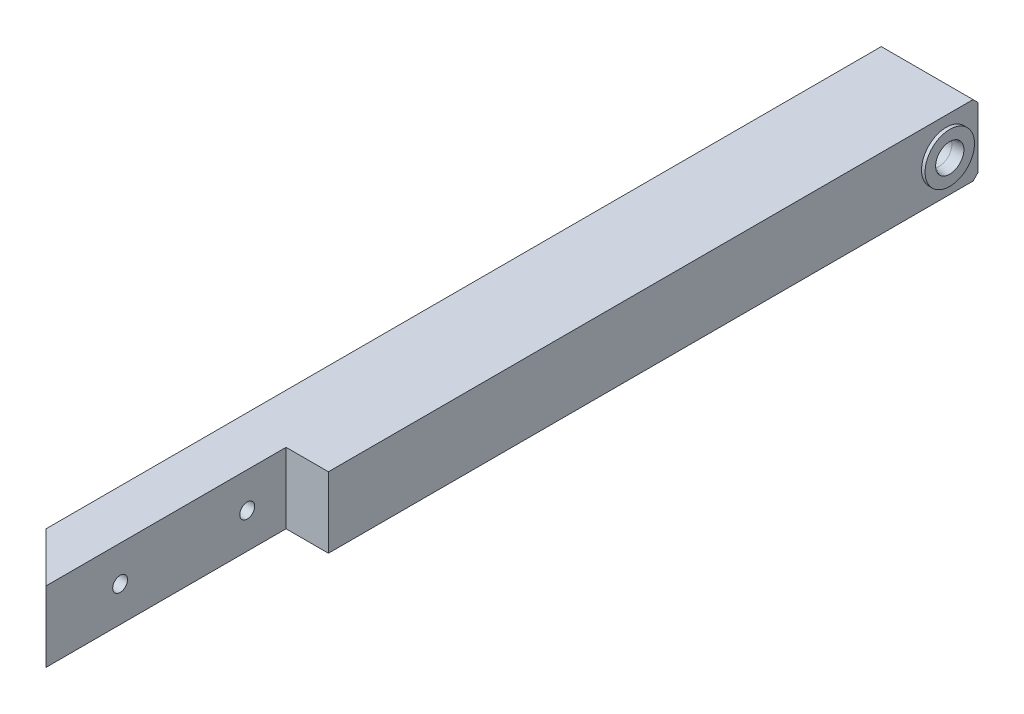
SolidWorks part; units mm, degrees
ref_plane "Front Plane" through (0, 0, 0) normal (0, 0, 1) x (1, 0, 0)
ref_plane "Top Plane" through (0, 0, 0) normal (0, 1, 0) x (1, 0, 0)
ref_plane "Right Plane" through (0, 0, 0) normal (1, 0, 0) x (0, 0, -1)
ref_plane "Plan1" through (0, 10, 0) normal (0, -1, 0) x (1, 0, 0)
sketch "Esquisse1" plane through (0, 10, 0) normal (0, -1, 0) x (1, 0, 0)
  line L0 (28, 25.5) -> (28, 151.5)
  line L1 (28, 151.5) -> (15, 151.5)
  line L2 (15, 151.5) -> (15, 25.5)
  line L3 (15, 25.5) -> (28, 25.5)
extrude "Boss.-Extru.1" add sketch "Esquisse1" against normal blind 10
sketch "Esquisse2" plane through (0, 20, 0) normal (0, 1, 0) x (-1, 0, 0)
  line L0 (-28, 117.5) -> (-22, 117.5)
  line L1 (-22, 117.5) -> (-22, 151.5)
  line L2 (-22, 151.5) -> (-28, 151.5)
  line L3 (-28, 151.5) -> (-28, 117.5)
extrude "Enlèv. mat.-Extru.1" cut sketch "Esquisse2" against normal through all
ref_plane "Plan2" through (0, 11.2, 0) normal (0, -1, 0) x (1, 0, 0)
sketch "Esquisse3" plane through (0, 11.2, 0) normal (0, -1, 0) x (1, 0, 0)
  line L0 (20.8533, 76.2777) -> (21.5573, 76.2788)
  line L1 (21.5573, 76.2788) -> (21.5614, 73.7372)
  line L2 (21.5614, 73.7372) -> (19.3376, 73.7336)
  line L3 (22.822, 73.8272) -> (22.6255, 74.5435)
  line L4 (19.736, 74.5148) -> (20.8533, 74.5148)
  line L5 (20.8533, 74.5148) -> (20.8533, 76.2777)
  arc A0 (19.3376, 73.7336) -> (18.633, 74.9446) centre (22.8239, 76.5726) cw
  spline S0 degree 3 poles (18.633, 74.9446) (18.5989, 75.0481) (18.5308, 75.2546) (18.4496, 75.5709) (18.4126, 75.8954) (18.4027, 76.1126) (18.3977, 76.2215) knots 0 0 0 0 0.250783 0.500014 0.749231 1 1 1 1
  spline S1 degree 3 poles (18.3977, 76.2215) (18.4047, 76.3608) (18.4187, 76.6379) (18.4758, 77.0511) (18.608, 77.4466) (18.72, 77.7004) (18.7763, 77.8279) knots 0 0 0 0 0.251459 0.500134 0.748674 1 1 1 1
  spline S2 degree 3 poles (18.7763, 77.8279) (18.8456, 77.94) (18.983, 78.1621) (19.2264, 78.4709) (19.5361, 78.7134) (19.7587, 78.8498) (19.8711, 78.9186) knots 0 0 0 0 0.2523 0.500035 0.747735 1 1 1 1
  spline S3 degree 3 poles (19.8711, 78.9186) (19.9984, 78.9736) (20.2516, 79.0829) (20.646, 79.2116) (21.0571, 79.2669) (21.3328, 79.2803) (21.4714, 79.287) knots 0 0 0 0 0.251271 0.49985 0.74858 1 1 1 1
  spline S4 degree 3 poles (21.4714, 79.287) (21.6125, 79.2798) (21.8935, 79.2654) (22.3125, 79.209) (22.7157, 79.0817) (22.9758, 78.9745) (23.1064, 78.9207) knots 0 0 0 0 0.251234 0.500055 0.748821 1 1 1 1
  spline S5 degree 3 poles (23.1064, 78.9207) (23.2212, 78.8559) (23.4486, 78.7275) (23.7669, 78.4969) (24.0197, 78.1957) (24.1621, 77.9771) (24.234, 77.8668) knots 0 0 0 0 0.252519 0.50023 0.747709 1 1 1 1
  spline S6 degree 3 poles (24.234, 77.8668) (24.2896, 77.7411) (24.4002, 77.4913) (24.5295, 77.101) (24.5836, 76.6935) (24.5961, 76.4203) (24.6023, 76.2829) knots 0 0 0 0 0.25132 0.499761 0.748442 1 1 1 1
  spline S7 degree 3 poles (24.6023, 76.2829) (24.5987, 76.1825) (24.5915, 75.9823) (24.5605, 75.6831) (24.4868, 75.3914) (24.4234, 75.2015) (24.3915, 75.1062) knots 0 0 0 0 0.250926 0.500139 0.749213 1 1 1 1
  spline S8 degree 3 poles (24.3915, 75.1062) (24.3561, 75.0281) (24.2856, 74.8729) (24.159, 74.6501) (23.991, 74.4565) (23.8668, 74.3401) (23.8042, 74.2815) knots 0 0 0 0 0.251757 0.500316 0.748557 1 1 1 1
  spline S9 degree 3 poles (23.8042, 74.2815) (23.7288, 74.2306) (23.5784, 74.1291) (23.3401, 73.9966) (23.084, 73.9028) (22.9096, 73.8525) (22.822, 73.8272) knots 0 0 0 0 0.250861 0.499685 0.748824 1 1 1 1
  spline S10 degree 3 poles (22.6255, 74.5435) (22.6892, 74.5636) (22.8161, 74.6037) (23.0028, 74.6749) (23.1784, 74.7704) (23.2899, 74.8428) (23.3458, 74.8791) knots 0 0 0 0 0.250917 0.500324 0.749408 1 1 1 1
  spline S11 degree 3 poles (23.3458, 74.8791) (23.3902, 74.9196) (23.4784, 75.0001) (23.5977, 75.1345) (23.6885, 75.2896) (23.7396, 75.3977) (23.7653, 75.4521) knots 0 0 0 0 0.251387 0.499614 0.748228 1 1 1 1
  spline S12 degree 3 poles (23.7653, 75.4521) (23.789, 75.5188) (23.8362, 75.6517) (23.8912, 75.8564) (23.9146, 76.067) (23.9201, 76.208) (23.9229, 76.2788) knots 0 0 0 0 0.250883 0.49987 0.748987 1 1 1 1
  spline S13 degree 3 poles (23.9229, 76.2788) (23.9205, 76.3592) (23.9157, 76.5194) (23.8924, 76.7589) (23.8341, 76.9923) (23.7829, 77.144) (23.7572, 77.2201) knots 0 0 0 0 0.251035 0.500251 0.749216 1 1 1 1
  spline S14 degree 3 poles (23.7572, 77.2201) (23.7297, 77.2794) (23.6749, 77.3974) (23.5794, 77.5679) (23.4567, 77.72) (23.3666, 77.8136) (23.3213, 77.8607) knots 0 0 0 0 0.251265 0.500229 0.748964 1 1 1 1
  spline S15 degree 3 poles (23.3213, 77.8607) (23.2759, 77.8985) (23.1854, 77.9739) (23.0427, 78.0784) (22.8878, 78.1639) (22.7813, 78.2141) (22.7278, 78.2392) knots 0 0 0 0 0.250691 0.500029 0.749338 1 1 1 1
  spline S16 degree 3 poles (22.7278, 78.2392) (22.6303, 78.2733) (22.4359, 78.3412) (22.137, 78.421) (21.8295, 78.4556) (21.6237, 78.4642) (21.5205, 78.4684) knots 0 0 0 0 0.250863 0.499917 0.749054 1 1 1 1
  spline S17 degree 3 poles (21.5205, 78.4684) (21.4047, 78.4648) (21.1744, 78.4575) (20.8305, 78.4196) (20.4985, 78.3218) (20.2852, 78.2355) (20.178, 78.1922) knots 0 0 0 0 0.251508 0.500429 0.74892 1 1 1 1
  spline S18 degree 3 poles (20.178, 78.1922) (20.095, 78.1419) (19.9306, 78.0424) (19.7021, 77.8646) (19.5246, 77.6359) (19.4258, 77.4712) (19.3759, 77.3879) knots 0 0 0 0 0.252519 0.500089 0.747569 1 1 1 1
  spline S19 degree 3 poles (19.3759, 77.3879) (19.3377, 77.2986) (19.2617, 77.1207) (19.1709, 76.8445) (19.13, 76.5567) (19.1193, 76.3636) (19.1139, 76.2665) knots 0 0 0 0 0.251263 0.49999 0.748727 1 1 1 1
  spline S20 degree 3 poles (19.1139, 76.2665) (19.1182, 76.1804) (19.1267, 76.0086) (19.1581, 75.7523) (19.2265, 75.5032) (19.2837, 75.3411) (19.3124, 75.2597) knots 0 0 0 0 0.250863 0.499972 0.74911 1 1 1 1
  spline S21 degree 3 poles (19.3124, 75.2597) (19.3403, 75.1934) (19.3959, 75.0612) (19.4898, 74.8675) (19.6064, 74.6865) (19.6927, 74.5722) (19.736, 74.5148) knots 0 0 0 0 0.250801 0.500326 0.749528 1 1 1 1
extrude "Enlèv. mat.-Extru.2" cut sketch "Esquisse3" against normal blind 0.4 from surface at 1.2 starting at face at (21.6667, 10, 98.1667)
sketch "Esquisse4" plane through (0, 10, 0) normal (0, -1, 0) x (1, 0, 0)
  line L0 (24.5, 84.1656) -> (18.5, 84.1656)
  line L1 (18.5, 84.1656) -> (18.5, 83.3716)
  line L2 (18.5, 83.3716) -> (21.2258, 83.3716)
  line L3 (21.2258, 83.3716) -> (21.2258, 80.5558)
  line L4 (21.2258, 80.5558) -> (21.9338, 80.5558)
  line L5 (21.9338, 80.5558) -> (21.9338, 83.3716)
  line L6 (21.9338, 83.3716) -> (23.792, 83.3716)
  line L7 (23.792, 83.3716) -> (23.792, 80.1178)
  line L8 (23.792, 80.1178) -> (24.5, 80.1178)
  line L9 (24.5, 80.1178) -> (24.5, 84.1656)
extrude "Enlèv. mat.-Extru.3" cut sketch "Esquisse4" against normal blind 0.4
sketch "Esquisse5" plane through (0, 10, 0) normal (0, -1, 0) x (1, 0, 0)
  line L0 (24.5, 69.7345) -> (18.5, 69.7345)
  line L1 (18.5, 69.7345) -> (18.5, 68.9405)
  line L2 (18.5, 68.9405) -> (21.2258, 68.9405)
  line L3 (21.2258, 68.9405) -> (21.2258, 66.1246)
  line L4 (21.2258, 66.1246) -> (21.9338, 66.1246)
  line L5 (21.9338, 66.1246) -> (21.9338, 68.9405)
  line L6 (21.9338, 68.9405) -> (23.792, 68.9405)
  line L7 (23.792, 68.9405) -> (23.792, 65.6867)
  line L8 (23.792, 65.6867) -> (24.5, 65.6867)
  line L9 (24.5, 65.6867) -> (24.5, 69.7345)
extrude "Enlèv. mat.-Extru.4" cut sketch "Esquisse5" against normal blind 0.4
sketch "Esquisse6" plane through (0, 10, 0) normal (0, -1, 0) x (1, 0, 0)
  line L0 (21.0416, 72.9473) -> (20.3008, 72.9473)
  line L1 (20.3008, 72.9473) -> (20.3008, 70.684)
  line L2 (20.3008, 70.684) -> (21.0416, 70.684)
  line L3 (21.0416, 70.684) -> (21.0416, 72.9473)
extrude "Enlèv. mat.-Extru.5" cut sketch "Esquisse6" against normal blind 0.4
draft "Dépouille1" type of draft neutral plane draft angle 0.092 faces to draft 1 face at (20.4495, 10.2, 73.7354) neutral plane through (21.6801, 10.4, 0.0349) neutral plane normal (-1, 0, -0.0016) reverse direction yes parameters "D1"=0.092
draft "Dépouille2" type of draft neutral plane draft angle 0.092 faces to draft 1 face at (21.2053, 10.2, 76.2782) neutral plane through (21.6801, 10.4, 0.0349) neutral plane normal (-1, 0, -0.0016) parameters "D1"=0.092
draft "Dépouille3" type of draft neutral plane draft angle 45 faces to draft 1 face at (18.5, 15, 151.5) neutral plane through (22, 10, 117.5) neutral plane normal (1, 0, 0) reverse direction yes parameters "D1"=45
ref_plane "Plan3" through (0, 0, 30) normal (0, 0, 1) x (1, 0, 0)
sketch "Esquisse7" plane through (0, 0, 30) normal (0, 0, 1) x (1, 0, 0)
  line L0 (28, 18.5) -> (28, 15)
  line L1 (28, 15) -> (28.5, 15)
  line L2 (28.5, 15) -> (28.5, 18.5)
  line L3 (28.5, 18.5) -> (28, 18.5)
  line L4 (28, 15) -> (28.5, 15) construction
revolve "Révolution1" add sketch "Esquisse7" angle 360 about L4
hole_wizard "Fraisage pour vis à tête fraisée M31" positions "Esquisse9" profile "Esquisse8" countersink size "M3" standard "Ansi Metric"
sketch "Esquisse9" plane through (28.5, 0, 0) normal (1, 0, 0) x (0, 0, -1)
  point P0 (-30, 15)
sketch "Esquisse8" plane through (28.5, 15, 30) normal (0, 1, 0) x (0, 0, -1)
  line L0 (0, 0) -> (0, 7)
  line L1 (0, 7) -> (1.8, 7)
  line L2 (1.8, 7) -> (1.8, 1.5)
  line L3 (1.8, 1.5) -> (2, 0)
  line L5 (2, 0) -> (0, 0)
  line L6 (-1.8, 1.5) -> (-2, 0) construction
  line L10 (0, 7) -> (-1.8, 7) construction
  line L11 (0, -6.35) -> (0, 107.95) construction
  dimension "Diamètre du perçage" = 3.6
  dimension "Profondeur du perçage" = 7
  dimension "Diamètre du fraisage entrant" = 4
  dimension "Angle du fraisage entrant" = 15.189
  dimension "Angle de pointe" = 180
hole_wizard "Diamètre du perçage Ø2.1 (2.1)1" positions "Esquisse11" profile "Esquisse10" hole size "Ø2.1" standard "Ansi Metric"
sketch "Esquisse11" plane through (22, 0, 0) normal (1, 0, 0) x (0, 0, -1)
  point P0 (-141, 15)
  point P1 (-123, 15)
sketch "Esquisse10" plane through (22, 15, 141) normal (0, 1, 0) x (0, 0, -1)
  line L0 (0, 0) -> (0, 5)
  line L1 (0, 5) -> (1.05, 5)
  line L2 (1.05, 5) -> (1.05, 0)
  line L5 (1.05, 0) -> (0, 0)
  line L10 (0, 5) -> (-1.05, 5) construction
  line L11 (0, -6.35) -> (0, 107.95) construction
  dimension "Diamètre du perçage" = 2.1
  dimension "Profondeur du perçage" = 5
  dimension "Angle de pointe" = 180
chamfer "Chanfrein1" distance 0.7 angle 45 2 edges at (21.5, 20, 25.5) (21.5, 10, 25.5)
